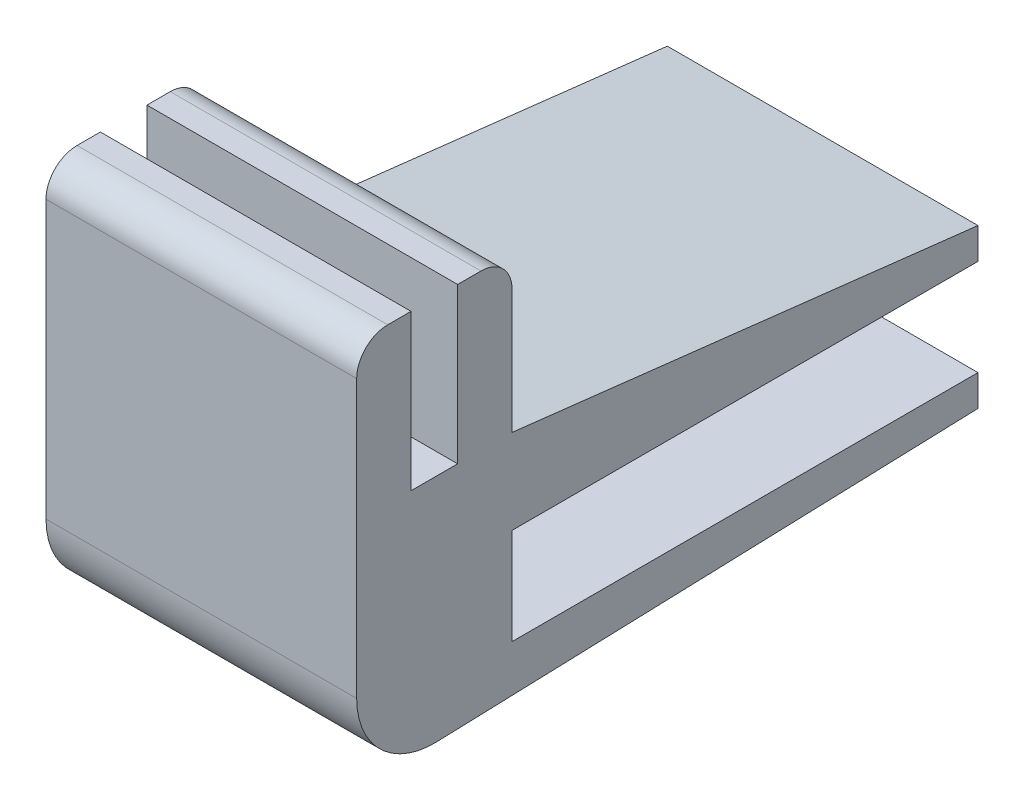
SolidWorks part; units mm, degrees
ref_plane "Plan de face" through (0, 0, 0) normal (0, 0, 1) x (1, 0, 0)
ref_plane "Plan de dessus" through (0, 0, 0) normal (0, 1, 0) x (1, 0, 0)
ref_plane "Plan de droite" through (0, 0, 0) normal (1, 0, 0) x (0, 0, -1)
sketch "Esquisse1" plane through (0, 0, 0) normal (1, 0, 0) x (0, 0, -1)
  line L0 (5.1669, 0.1725) -> (40, 1.3356)
  line L1 (40, 1.3356) -> (40, 3.3356)
  line L2 (40, 3.3356) -> (10, 3.3356)
  line L3 (10, 3.3356) -> (10, 9.5356)
  line L4 (10, 9.5356) -> (40, 9.5356)
  line L5 (40, 9.5356) -> (40, 11.5356)
  line L6 (0, 15) -> (0, 23)
  line L7 (0, 15) -> (0, 5.1697)
  line L8 (10, 15) -> (10, 23)
  line L9 (8, 25) -> (6.5, 25)
  line L10 (6.5, 25) -> (6.5, 15)
  line L11 (6.5, 15) -> (3.5, 15)
  line L12 (3.5, 15) -> (3.5, 25)
  line L13 (3.5, 25) -> (2, 25)
  line L14 (10, 15) -> (40, 11.5356)
  arc A0 (5.1669, 0.1725) -> (0, 5.1697) centre (5, 5.1697) cw
  arc A1 (10, 23) -> (8, 25) centre (8, 23) ccw
  arc A2 (0, 23) -> (2, 25) centre (2, 23) cw
  point P18 (0, 0)
  dimension "D9" = 5
  dimension "D10" = 2
  dimension "D1" = 30
  dimension "D2" = 2
  dimension "D3" = 2
  dimension "D4" = 6.2
  dimension "D5" = 3
  dimension "D6" = 15
  dimension "D7" = 3
  dimension "40" = 40
  dimension "D8" = 10
extrude "Boss.-Extru.1" add sketch "Esquisse1" along normal blind 20
